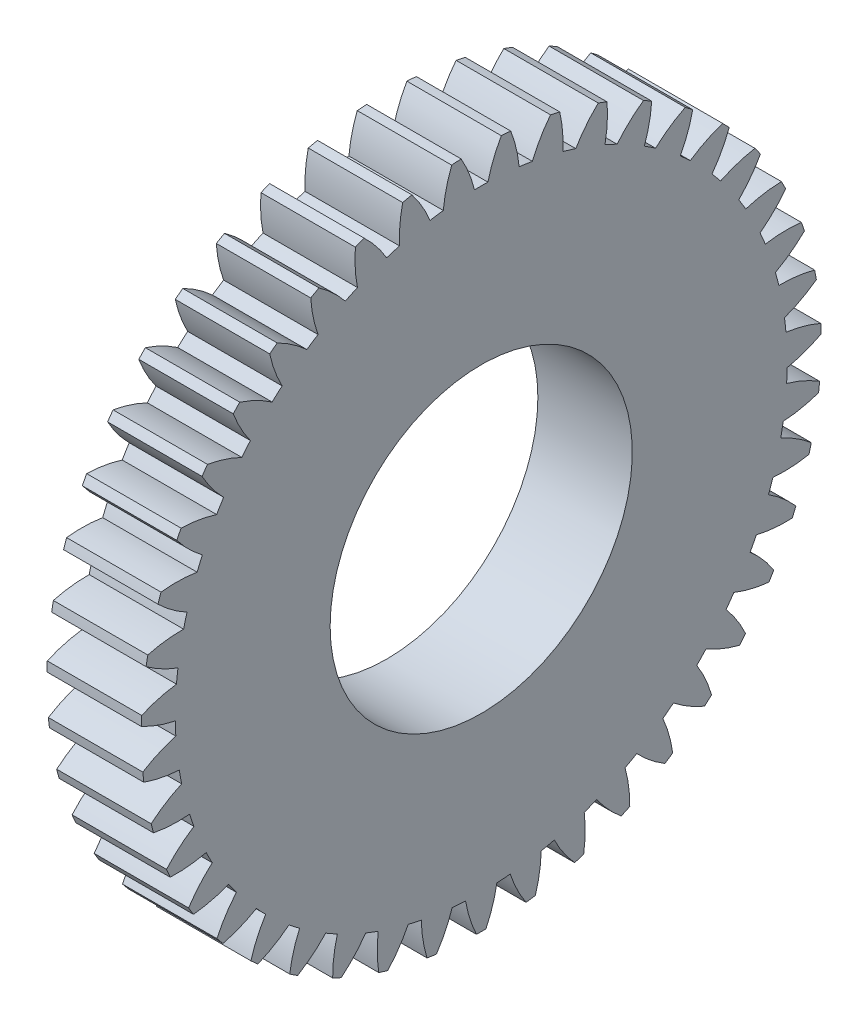
SolidWorks part; units mm, degrees
ref_plane "Plane1" through (0, 0, 0) normal (0, 0, 1) x (1, 0, 0)
ref_plane "Plane2" through (0, 0, 0) normal (0, 1, 0) x (1, 0, 0)
ref_plane "Plane3" through (0, 0, 0) normal (1, 0, 0) x (0, 0, -1)
sketch "HoldingSke" plane through (0, 0, 0) normal (0, 1, 0) x (1, 0, 0)
  line L0 (0, 0) -> (1.8284, -1.705)
  line L1 (-15, 0) -> (100, 0) construction
  line L2 (0, 0) -> (-2.1039, 2.3779)
  line L3 (0, 0) -> (-11.863, 4.5341)
  line L4 (0, 0) -> (6.316, 5.8897)
  line L5 (0, 0) -> (-46.8476, -17.4728)
  line L6 (0, 0) -> (-2.0724, -1.3983)
  line L7 (-2.1039, 2.3779) -> (8.6586, 51.2059)
  line L8 (-76.2, 54.61) -> (-74.8, 54.61)
  line L9 (-71.009, 38.7566) -> (-53.1078, 45.2721)
  line L10 (-76.2, 71.12) -> (104.1128, 71.12)
  line L11 (0, 0) -> (-2.5, 0)
  line L12 (-76.2, 101.6) -> (-76.185, 101.6)
  line L13 (24.9733, 27.94) -> (52.9518, 28.4284)
  line L14 (24.9733, 27.94) -> (24.9743, 27.94)
  line L15 (24.9733, 27.94) -> (100.4006, 29.5858)
  line L16 (-63.627, -0.4) -> (-12.827, -0.4)
  circle A0 centre (0, 0) radius 4
  circle A1 centre (0, 0) radius 8.099
  circle A2 centre (0, 0) radius 37.5
  circle A3 centre (0, 0) radius 4
  dimension "MHD" = 16.198
  dimension "Hub_dia" = 75
  dimension "Bore" = 8
  dimension "MBD" = 8
  dimension "Num_teeth" = 43
  dimension "Pitch" = 2.5
  dimension "Overall_len" = 50
  dimension "Show_teeth" = 43
  dimension "Thickness" = 2.5
  dimension "OAL" = 50.0001
  dimension "T_dim" = 1.4
  dimension "Ap" = 20
  dimension "H" = 19.05
  dimension "Pitch_radius" = 180.3128
  dimension "Width" = 2.5
  dimension "Backlash" = 0.015
  dimension "Addendum_fac" = 1
  dimension "Dedendum_fac" = 1.25
  dimension "Clearance_fac" = 0.25
  dimension "Dedendum_add" = 0.001
  dimension "Module" = 0.4
sketch "BasProSke" plane through (0, 0, 0) normal (0, 1, 0) x (1, 0, 0)
  line L0 (-10, 0) -> (60, 0) construction
  line L1 (0, 0) -> (0, 9)
  line L2 (0, 0) -> (2.5, 0)
  line L3 (2.5, 0) -> (2.5, 9)
  line L4 (2.5, 9) -> (0, 9)
  dimension "Thickness" = 2.5
  dimension "Diameter" = 18
revolve "Base-Revolve" add sketch "BasProSke" angle 360 about L0
sketch "TooCutSke" plane through (0, 0, 0) normal (1, 0, 0) x (0, 0, -1)
  line L1 (0, 0) -> (0, 107) construction
  line L2 (0, 0) -> (-0.3403, 8.5933) construction
  line L3 (0, 0) -> (-1.2548, 17.1445) construction
  line L4 (-0.3403, 8.5933) -> (-0.6274, 8.5723) construction
  arc A0 (0.1775, 8.0971) -> (-0.1775, 8.0971) centre (0, 0) ccw
  arc A1 (0.5465, 9.0088) -> (-0.5465, 9.0088) centre (0, 0) ccw
  circle A2 centre (0, 0) radius 8.6 construction
  circle A3 centre (0, 0) radius 8.0814 construction
  arc A4 (-0.1775, 8.0971) -> (-0.5465, 9.0088) centre (-3.5179, 7.2755) ccw
  arc A5 (0.5465, 9.0088) -> (0.1775, 8.0971) centre (3.5179, 7.2755) ccw
  dimension "Root_dia" = 16.198
  dimension "Overcut_dia" = 18.0508
  dimension "Pitch_dia" = 17.2
  dimension "Base_dia" = 16.1627
  dimension "Flank_rad" = 3.44
  dimension "Half_ang" = 4.186
  dimension "Half_CT" = 0.2878
extrude "ToothCut" cut sketch "TooCutSke" along normal through all
fillet "Breaks" [suppressed] radius 0.008
fillet "RootFillets" [suppressed] radius 0.101
pattern_circular "TeethCuts" count 43 every 8.372 about axis through (-10, 0, 0) along (1, 0, 0) of "ToothCut", "RootFillets", "Breaks"
sketch "HubNeaOneSke" plane through (0, 0, 0) normal (-1, 0, 0) x (0, 0, 1)
  circle A0 centre (0, 0) radius 8.099
  dimension "Diameter" = 16.198
extrude "HubNearOne" [suppressed] add sketch "HubNeaOneSke" along normal blind 47.5001
sketch "HubNeaBotSke" plane through (0, 0, 0) normal (-1, 0, 0) x (0, 0, 1)
  circle A0 centre (0, 0) radius 8.099
  dimension "Diameter" = 16.198
extrude "HubNearBoth" [suppressed] add sketch "HubNeaBotSke" along normal blind 23.75
ref_plane "FarPln" through (2.5, 0, 0) normal (1, 0, 0) x (0, 0, -1)
sketch "HubFarSke" plane through (2.5, 0, 0) normal (1, 0, 0) x (0, 0, -1)
  circle A0 centre (0, 0) radius 8.099
  dimension "Diameter" = 16.198
extrude "HubFar" [suppressed] add sketch "HubFarSke" along normal blind 23.75
sketch "BorSke" plane through (0, 0, 0) normal (1, 0, 0) x (0, 0, -1)
  circle A0 centre (0, 0) radius 4
  dimension "Diameter" = 8
extrude "Bore" cut sketch "BorSke" along normal mid plane 100.0001
sketch "KeySke" plane through (0, 0, 0) normal (1, 0, 0) x (0, 0, -1)
  line L0 (-1.5, 0) -> (-1.5, 5.4)
  line L1 (-1.5, 5.4) -> (1.5, 5.4)
  line L2 (1.5, 5.4) -> (1.5, 0)
  line L3 (0, 0) -> (0, 34) construction
  line L4 (-1.5, 0) -> (1.5, 0)
  dimension "Offset" = 5.4
  dimension "Width" = 3
extrude "Keyway" [suppressed] cut sketch "KeySke" along normal mid plane 100.0001
pattern_circular "Keyway2" [suppressed] count 2 every 90 about axis through (-10, 0, 0) along (1, 0, 0)
equation "' \"Module@HoldingSke\" = 6.35"
equation "' \"Num_teeth@HoldingSke\" = 12"
equation "' \"Ap@HoldingSke\" =  20"
equation "' \"Ap@HoldingSke\" = 20"
equation "' \"Width@HoldingSke\" = 0.5 * 25.4"
equation "' \"Hub_dia@HoldingSke\"= 1 * 25.4"
equation "' \"Hub_dia@HoldingSke\" = 1 * 25.4"
equation "' \"Overall_len@HoldingSke\" = 1.0 * 25.4"
equation "' \"Bore@HoldingSke\" = 0.75 * 25.4"
equation "' \"T_dim@HoldingSke\" = 0.1 * 25.4"
equation "' \"Width@KeySke\" = 0.25 * 25.4"
equation "' \"Show_teeth@HoldingSke\" = 13"
equation "' \"Backlash@HoldingSke\" = 0.009 * 25.4"
equation "' \"Addendum_fac@HoldingSke\" = 1.0"
equation "' \"Dedendum_fac@HoldingSke\" = 1.25"
equation "' \"Dedendum_add@HoldingSke\" = 0.00005 * 25.4"
equation "' \"Clearance_fac@HoldingSke\" = 0.25"
equation "\"Pitch@HoldingSke\" = 1 / \"Module@HoldingSke\""
equation "\"Overcut_dia@TooCutSke\" = (\"Num_teeth@HoldingSke\" + 2 * \"Addendum_fac@HoldingSke\") / \"Pitch@HoldingSke\" + 0.002 * 25.4"
equation "\"Pitch_dia@TooCutSke\" = \"Num_teeth@HoldingSke\" / \"Pitch@HoldingSke\""
equation "\"Base_dia@TooCutSke\" = \"Num_teeth@HoldingSke\" / \"Pitch@HoldingSke\" * cos((\"Ap@HoldingSke\"  * 3.14159265 / 180))"
equation "\"Root_dia@TooCutSke\" = (\"Num_teeth@HoldingSke\" + 2) / \"Pitch@HoldingSke\" - 2 * (\"Addendum_fac@HoldingSke\" + \"Dedendum_fac@HoldingSke\") / \"Pitch@HoldingSke\" - \"Dedendum_add@HoldingSke\" * 2"
equation "\"Half_ang@TooCutSke\" = 180 / \"Num_teeth@HoldingSke\""
equation "\"Half_CT@TooCutSke\" = \"Num_teeth@HoldingSke\" / \"Pitch@HoldingSke\" * sin((3.14159265 / 2 / \"Num_teeth@HoldingSke\")) / 2 - 7 * \"Backlash@HoldingSke\" / 4"
equation "\"Flank_rad@TooCutSke\" = \"Num_teeth@HoldingSke\" / \"Pitch@HoldingSke\" / 5"
equation "\"Radius@RootFillets\" = \"Clearance_fac@HoldingSke\" / \"Pitch@HoldingSke\" + \"Dedendum_add@HoldingSke\""
equation "\"Break_rad@Breaks\" = 0.02 / \"Pitch@HoldingSke\""
equation "\"Thickness@HoldingSke\" = \"Width@HoldingSke\""
equation "\"OAL@HoldingSke\" = \"Thickness@HoldingSke\""
equation "\"MHD@HoldingSke\" = (\"Num_teeth@HoldingSke\" + 2) / \"Pitch@HoldingSke\" - 2 * (\"Addendum_fac@HoldingSke\" + \"Dedendum_fac@HoldingSke\")  / \"Pitch@HoldingSke\" - \"Dedendum_add@HoldingSke\" * 2"
equation "\"MBD@HoldingSke\" = (\"Num_teeth@HoldingSke\" + 2) / \"Pitch@HoldingSke\" - 2 * (\"Addendum_fac@HoldingSke\" + \"Dedendum_fac@HoldingSke\")  / \"Pitch@HoldingSke\" - \"Dedendum_add@HoldingSke\" * 2 - 0.002 * 25.4"
equation "\"MHD@HoldingSke\" = ((sgn( \"MHD@HoldingSke\" - \"Hub_dia@HoldingSke\" )-1)*( \"MHD@HoldingSke\" - \"Hub_dia@HoldingSke\" ))/-2+ \"Hub_dia@HoldingSke\""
equation "\"MBD@HoldingSke\" = ((sgn( \"MBD@HoldingSke\" - \"Bore@HoldingSke\" )-1)*( \"MBD@HoldingSke\" - \"Bore@HoldingSke\" ))/-2+ \"Bore@HoldingSke\""
equation "\"OAL@HoldingSke\" = ((sgn( \"OAL@HoldingSke\" - \"Overall_len@HoldingSke\" )+1)*( \"OAL@HoldingSke\" - \"Overall_len@HoldingSke\" ))/2 + \"Overall_len@HoldingSke\" + 0.000002 * 25.4"
equation "\"Num_teeth@TeethCuts\" = int( \"Show_teeth@HoldingSke\" ) + 1"
equation "\"Num_teeth@TeethCuts\" = ((sgn( \"Num_teeth@TeethCuts\" - \"Num_teeth@HoldingSke\" )-1)*( \"Num_teeth@TeethCuts\" - \"Num_teeth@HoldingSke\" ))/-2+ \"Num_teeth@HoldingSke\""
equation "\"Num_teeth@TeethCuts\" = ((sgn( \"Num_teeth@TeethCuts\" - 2.0)+1)*( \"Num_teeth@TeethCuts\" - 2.0))/2 +2.0"
equation "\"Angle@TeethCuts\" = 360.0 / \"Num_teeth@HoldingSke\""
equation "\"Diameter@BasProSke\" = (\"Num_teeth@HoldingSke\" + 2 * \"Addendum_fac@HoldingSke\") / \"Pitch@HoldingSke\""
equation "\"Thickness@BasProSke\"  = \"Thickness@HoldingSke\""
equation "' \"Fillet_rad@BasProSke\" =  \"Thickness@HoldingSke\" * 0.05"
equation "' \"Fillet_rad@BasProSke\" = \"Thickness@HoldingSke\" * 0.05"
equation "\"MHD@HoldingSke\" = ((sgn( \"MHD@HoldingSke\" - \"Root_dia@TooCutSke\" )-1)*( \"MHD@HoldingSke\" - \"Root_dia@TooCutSke\" ))/-2+ \"Root_dia@TooCutSke\""
equation "\"Diameter@HubNeaOneSke\" = \"MHD@HoldingSke\""
equation "\"Length@HubNearOne\" = \"OAL@HoldingSke\" - \"Thickness@BasProSke\""
equation "\"Diameter@HubNeaBotSke\" = \"MHD@HoldingSke\""
equation "\"Length@HubNearBoth\" = ( \"OAL@HoldingSke\" - \"Thickness@BasProSke\" ) / 2.0"
equation "\"Thickness@FarPln\" = \"Thickness@BasProSke\""
equation "\"Diameter@HubFarSke\" = \"MHD@HoldingSke\""
equation "\"Length@HubFar\" = ( \"OAL@HoldingSke\" - \"Thickness@BasProSke\" ) / 2.0"
equation "\"Diameter@BorSke\" = \"MBD@HoldingSke\""
equation "\"D1@Bore\" = \"OAL@HoldingSke\" * 2.0"
equation "\"D1@Keyway\" = \"OAL@HoldingSke\" * 2.0"
equation "\"Offset@KeySke\" = \"T_dim@HoldingSke\" + \"MBD@HoldingSke\" / 2.0"
